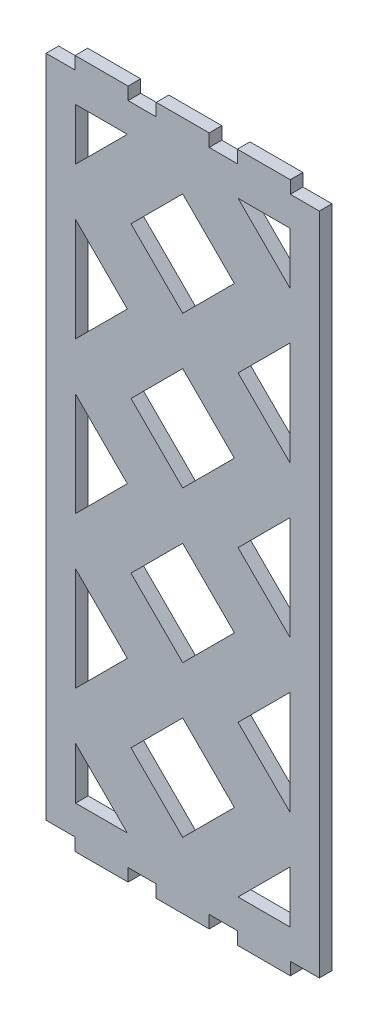
SolidWorks part; units mm, degrees
ref_plane "Alzado" through (0, 0, 0) normal (0, 0, 1) x (1, 0, 0)
ref_plane "Planta" through (0, 0, 0) normal (0, 1, 0) x (1, 0, 0)
ref_plane "Vista lateral" through (0, 0, 0) normal (1, 0, 0) x (0, 0, -1)
sketch "Croquis1" plane through (0, 0, 0) normal (0, 1, 0) x (1, 0, 0)
  line L1 (-65, 0) -> (-32.5, -56.2917) construction
  line L2 (-32.5, -56.2917) -> (32.5, -56.2917) construction
  line L3 (32.5, -56.2917) -> (65, 0) construction
  line L4 (65, 0) -> (32.5, 56.2917) construction
  line L5 (32.5, 56.2917) -> (-32.5, 56.2917) construction
  line L6 (-32.5, 56.2917) -> (-65, 0) construction
  circle A0 centre (0, 0) radius 56.2917 construction
  dimension "D1" = 65
sketch "Croquis2" plane through (0, 0, 0) normal (0, 0, 1) x (1, 0, 0)
  line L0 (-32.5, 0) -> (-25.6, 0)
  line L1 (-6.3, 3) -> (-6.3, 0)
  line L3 (-32.5, 0) -> (-32.5, -158)
  line L4 (32.5, 0) -> (32.5, -158)
  line L5 (-32.5, -158) -> (-25.6, -158)
  line L6 (32.5, 0) -> (-32.5, 0) construction
  line L7 (-32.5, 0) -> (-65, 0) construction
  line L8 (32.5, 0) -> (65, 0) construction
  line L9 (6.3, 0) -> (13, 0)
  line L14 (6.3, -161) -> (6.3, -158)
  line L15 (6.3, 3) -> (-6.3, 3)
  line L16 (-25.6, 0) -> (-13, 0) construction
  line L17 (-25.6, 3) -> (-13, 3)
  line L18 (-25.6, 3) -> (-25.6, 0)
  line L19 (-25.6, 0) -> (-13, 0) construction
  line L20 (-13, 3) -> (-13, 0)
  line L21 (-25.6, 3) -> (-13, 0) construction
  line L22 (-25.6, 0) -> (-13, 3) construction
  line L23 (-13, 0) -> (-6.3, 0)
  line L24 (0, 5.6059) -> (0, 3) construction
  line L28 (13, 0) -> (25.6, 0) construction
  line L29 (25.6, 0) -> (32.5, 0)
  line L38 (-25.475, -158) -> (-13.175, -158) construction
  line L39 (-13, -158) -> (-6.3, -158)
  line L40 (-6.15, -158) -> (6.15, -158) construction
  line L41 (6.3, -158) -> (13, -158)
  line L42 (13.175, -158) -> (25.475, -158) construction
  line L43 (25.6, -158) -> (32.5, -158)
  line L48 (-13.175, -7.03) -> (-25.475, -19.33)
  line L49 (-13.175, -7.03) -> (-25.475, -7.03)
  line L50 (-25.475, -7.03) -> (-25.475, -19.33)
  line L51 (13.175, -7.03) -> (25.475, -7.03)
  line L52 (13.175, -7.03) -> (25.475, -19.33)
  line L53 (25.475, -7.03) -> (25.475, -19.33)
  line L54 (13.175, -79) -> (25.475, -66.7)
  line L55 (13.175, -150.97) -> (25.475, -138.67)
  line L56 (25.475, -91.3) -> (25.475, -66.7)
  line L59 (-13.175, -79) -> (-25.475, -66.7)
  line L60 (-25.475, -91.3) -> (-25.475, -66.7)
  line L61 (13.175, -43.015) -> (25.475, -55.315)
  line L62 (25.475, -150.97) -> (25.475, -138.67)
  line L63 (13.175, -43.015) -> (25.475, -30.715)
  line L64 (25.475, -55.315) -> (25.475, -30.715)
  line L67 (-13.175, -43.015) -> (-25.475, -30.715)
  line L68 (-25.475, -55.315) -> (-25.475, -30.715)
  line L69 (-13.175, -43.015) -> (-25.475, -55.315)
  line L73 (0, -48.7075) -> (-12.3, -61.0075)
  line L74 (-12.3, -61.0075) -> (0, -73.3075)
  line L75 (0, -73.3075) -> (12.3, -61.0075)
  line L76 (12.3, -61.0075) -> (0, -48.7075)
  line L78 (13.175, -150.97) -> (25.475, -150.97)
  line L79 (0, -12.7225) -> (12.3, -25.0225)
  line L80 (-12.3, -25.0225) -> (0, -12.7225)
  line L81 (0, -37.3225) -> (-12.3, -25.0225)
  line L82 (12.3, -25.0225) -> (0, -37.3225)
  line L83 (-13.175, -150.97) -> (-25.475, -150.97)
  line L84 (-13.175, -150.97) -> (-25.475, -138.67)
  line L85 (-25.475, -150.97) -> (-25.475, -138.67)
  line L86 (-13.175, -114.985) -> (-25.475, -127.285)
  line L87 (-25.475, -102.685) -> (-25.475, -127.285)
  line L88 (-13.175, -114.985) -> (-25.475, -102.685)
  line L89 (-12.3, -132.9775) -> (0, -145.2775)
  line L90 (0, -120.6775) -> (-12.3, -132.9775)
  line L91 (12.3, -132.9775) -> (0, -120.6775)
  line L92 (0, -145.2775) -> (12.3, -132.9775)
  line L93 (13.175, -114.985) -> (25.475, -127.285)
  line L94 (25.475, -102.685) -> (25.475, -127.285)
  line L95 (13.175, -114.985) -> (25.475, -102.685)
  line L96 (13.175, -79) -> (25.475, -91.3)
  line L97 (0, -84.6925) -> (12.3, -96.9925)
  line L98 (-12.3, -96.9925) -> (0, -84.6925)
  line L99 (0, -109.2925) -> (-12.3, -96.9925)
  line L100 (12.3, -96.9925) -> (0, -109.2925)
  line L101 (-13.175, -79) -> (-25.475, -91.3)
  line L102 (-32.5, -79) -> (114.2784, -79) construction
  line L103 (-13, -161) -> (-13, -158)
  line L104 (-25.6, -161) -> (-13, -161)
  line L105 (-25.6, -161) -> (-25.6, -158)
  line L106 (6.3, 3) -> (6.3, 0)
  line L107 (6.3, -161) -> (-6.3, -161)
  line L108 (-6.3, -161) -> (-6.3, -158)
  line L109 (13, 3) -> (13, 0)
  line L110 (25.6, 3) -> (25.6, 0)
  line L111 (25.6, 3) -> (13, 3)
  line L112 (25.6, -161) -> (25.6, -158)
  line L113 (25.6, -161) -> (13, -161)
  line L114 (13, -161) -> (13, -158)
  point P10 (0, 1.5)
  point P15 (-19.3, 1.5)
  point P41 (-25.475, -7.03)
  dimension "D1" = 158
  dimension "D2" = 6.3
  dimension "D5" = 3
  dimension "D7" = 7.03
  dimension "D8" = 6.3
  dimension "D9" = 12.3
  dimension "D10" = 6.9
  dimension "D12" = 13.2
extrude "Saliente-Extruir1" add sketch "Croquis2" along normal blind 3
